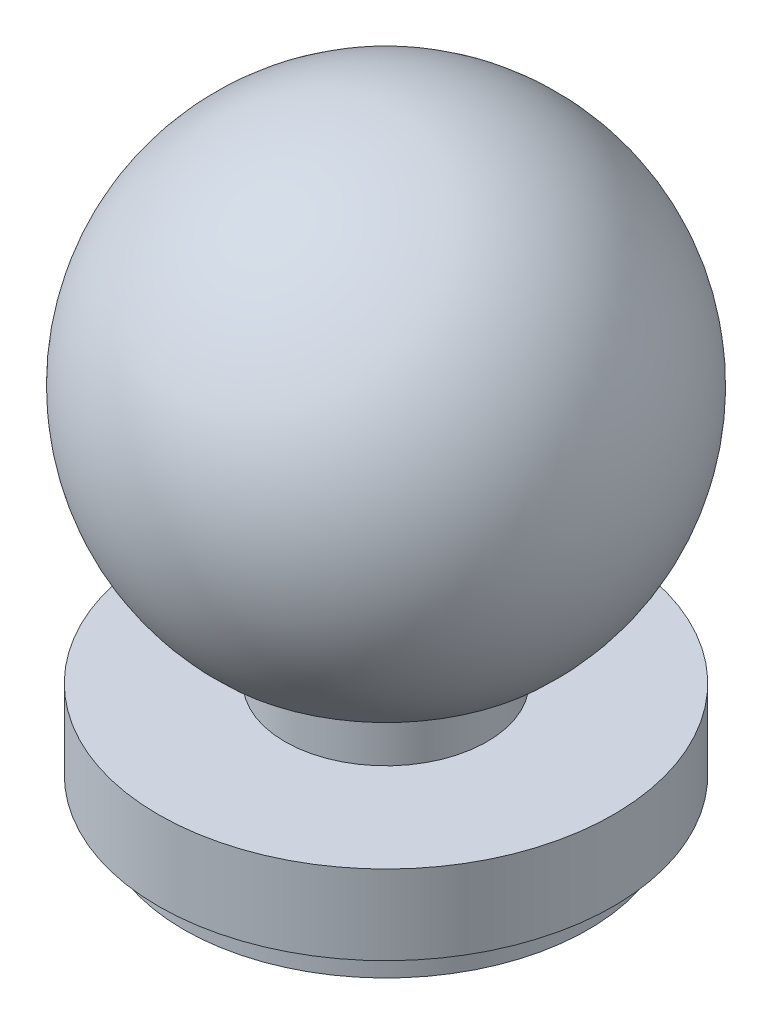
SolidWorks part; units mm, degrees
ref_plane "Front Plane" through (0, 0, 0) normal (0, 0, 1) x (1, 0, 0)
ref_plane "Top Plane" through (0, 0, 0) normal (0, 1, 0) x (1, 0, 0)
ref_plane "Right Plane" through (0, 0, 0) normal (1, 0, 0) x (0, 0, -1)
sketch "Sketch1" plane through (0, 0, 0) normal (0, 1, 0) x (1, 0, 0)
  circle A0 centre (0, 0) radius 4.5
  dimension "D1" = 9
extrude "Boss-Extrude1" add sketch "Sketch1" along normal blind 1.57
sketch "Sketch2" plane through (0, 1.57, 0) normal (0, 1, 0) x (1, 0, 0)
  circle A0 centre (0, 0) radius 2
  dimension "D1" = 4
extrude "Boss-Extrude2" add sketch "Sketch2" along normal blind 5.1
sketch "Sketch3" plane through (0, 6.67, 0) normal (0, 1, 0) x (1, 0, 0)
  line L0 (0, 8.312) -> (0, -16.0573) construction
  line L1 (0, 4.75) -> (0, -4.75)
  arc A0 (0, -4.75) -> (0, 4.75) centre (0, 0) ccw
  dimension "D1" = 4.75
revolve "Revolve1" add sketch "Sketch3" angle 360 about L0
sketch "Sketch5" plane through (0, 0, 0) normal (0, 0, 1) x (1, 0, 0)
  line L0 (0, 3.1597) -> (3.2, 3.1597) construction
  line L1 (3.2, 3.1597) -> (3.2, 2.3616)
  line L2 (3.2, 2.3616) -> (2, 2.3616)
  line L3 (2, 1.57) -> (2, 2.3616) construction
  line L4 (2, 2.3616) -> (2, 3.1597)
  line L5 (0, 3.1597) -> (0, 0) construction
  line L6 (2, 2.3616) -> (-2, 2.3616) construction
  line L7 (2, 3.1597) -> (3.2, 3.1597)
  arc A0 (2, 2.3616) -> (-2, 2.3616) centre (0, 6.67) ccw construction
  dimension "D1" = 3.2
revolve "Cut-Revolve1" cut sketch "Sketch5" angle 360 about L5
sketch "Sketch4" plane through (0, 0, 0) normal (0, -1, 0) x (1, 0, 0)
  circle A0 centre (0, 0) radius 4
  dimension "D1" = 8
extrude "Boss-Extrude3" add sketch "Sketch4" along normal blind 0.65
ref_point "Point1"
